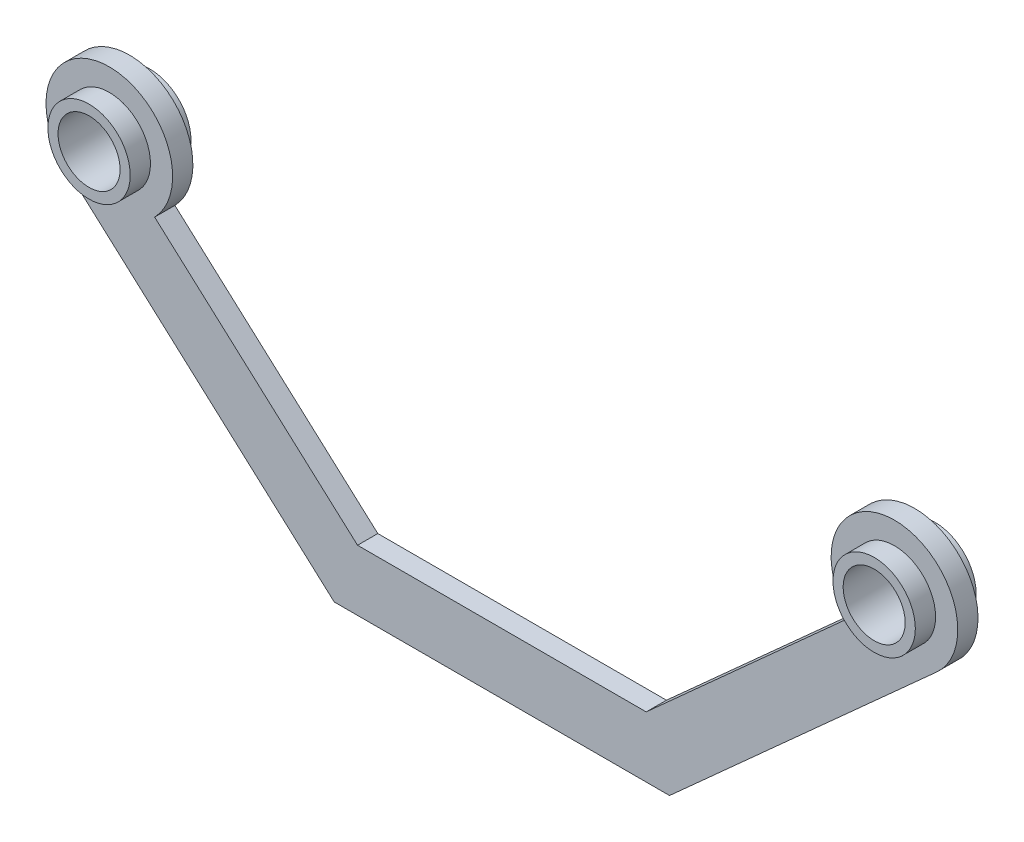
SolidWorks part; units mm, degrees
ref_plane "Front Plane" through (0, 0, 0) normal (0, 0, 1) x (1, 0, 0)
ref_plane "Top Plane" through (0, 0, 0) normal (0, 1, 0) x (1, 0, 0)
ref_plane "Right Plane" through (0, 0, 0) normal (1, 0, 0) x (0, 0, -1)
sketch "Sketch1" plane through (0, 0, 0) normal (0, 0, 1) x (1, 0, 0)
  line L0 (0, 0) -> (0, -56.8) construction
  line L1 (-77.5, 0) -> (0, 0) construction
  line L2 (-33.0982, -56.8) -> (-0.2147, -56.8) construction
  line L3 (-28.4918, -44.8) -> (-0.2147, -44.8) construction
  line L4 (85.8641, -9.2893) -> (33.0982, -56.8)
  line L5 (-68.5527, -8.729) -> (-28.4918, -44.8)
  line L6 (-28.4918, -44.8) -> (28.4918, -44.8)
  line L7 (-85.8641, -9.2893) -> (-33.0982, -56.8)
  line L8 (-33.0982, -56.8) -> (33.0982, -56.8)
  line L9 (-74.5417, -3.3365) -> (-28.4918, -44.8) construction
  line L10 (-82.5713, -12.2542) -> (-33.0982, -56.8) construction
  line L11 (68.5527, -8.729) -> (28.4918, -44.8)
  circle A0 centre (-77.5, 0) radius 6.25
  arc A1 (-68.5527, -8.729) -> (-85.8641, -9.2893) centre (-77.5, 0) ccw
  arc A2 (68.5527, -8.729) -> (85.8641, -9.2893) centre (77.5, 0) cw
  circle A3 centre (77.5, 0) radius 6.25
  point P15 (0, -44.8)
  dimension "D1" = 12.5
  dimension "D2" = 25
  dimension "D3" = 56.8
  dimension "D4" = 138
  dimension "D5" = 12
extrude "Boss-Extrude1" add sketch "Sketch1" along normal blind 4
sketch "Sketch7" plane through (0, 0, 4) normal (0, 0, 1) x (1, 0, 0)
  circle A0 centre (-77.5, 0) radius 6.125
  circle A1 centre (-77.5, 0) radius 8.125
  dimension "D1" = 12.25
  dimension "D2" = 16.25
extrude "Boss-Extrude5" add sketch "Sketch7" along normal blind 4 and the other way blind 8
mirror "Mirror1" about plane through (0, 0, 0) normal (1, 0, 0) of "Boss-Extrude5"
